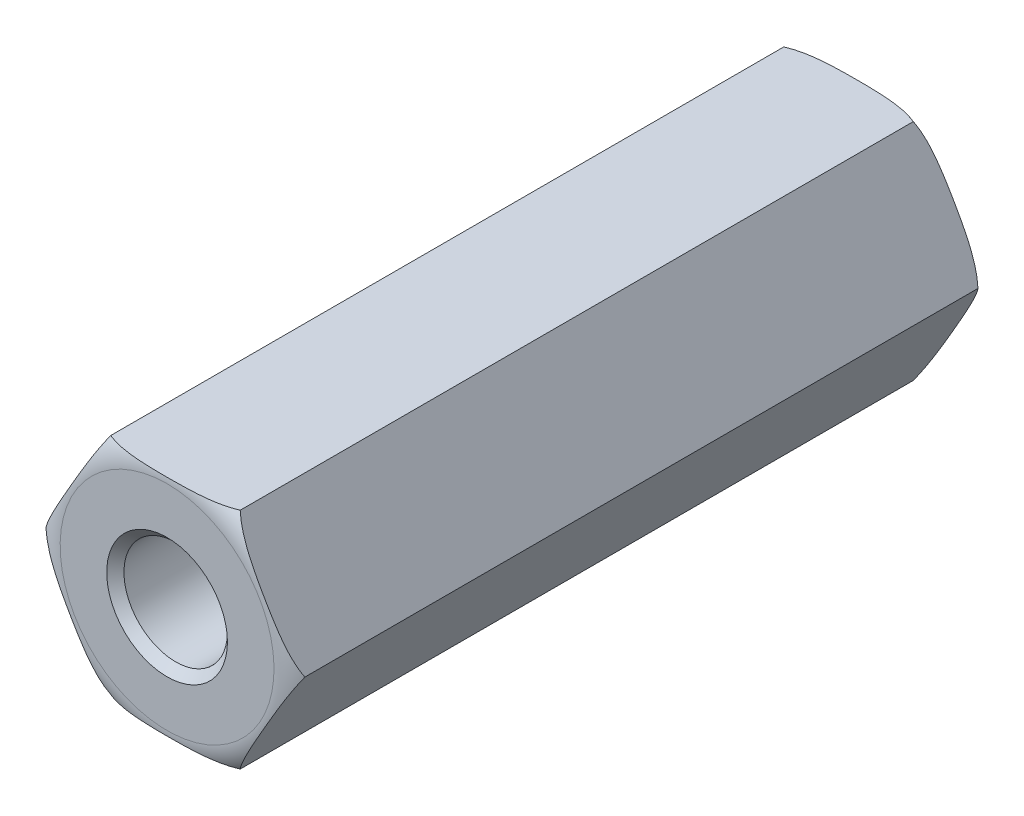
SolidWorks part; units mm, degrees
ref_plane "Front Plane" through (0, 0, 0) normal (0, 0, 1) x (1, 0, 0)
ref_plane "Top Plane" through (0, 0, 0) normal (0, 1, 0) x (1, 0, 0)
ref_plane "Right Plane" through (0, 0, 0) normal (1, 0, 0) x (0, 0, -1)
sketch "Sketch2" plane through (0, 0, 0) normal (0, 0, 1) x (1, 0, 0)
  circle A0 centre (0, 0) radius 1.5
  dimension "D1" = 3
sketch "Sketch3" plane through (0, 0, 0) normal (0, 0, 1) x (1, 0, 0)
  line L1 (3.7528, 0) -> (1.8764, 3.25)
  line L2 (1.8764, 3.25) -> (-1.8764, 3.25)
  line L3 (-1.8764, 3.25) -> (-3.7528, 0)
  line L4 (-3.7528, 0) -> (-1.8764, -3.25)
  line L5 (-1.8764, -3.25) -> (1.8764, -3.25)
  line L6 (1.8764, -3.25) -> (3.7528, 0)
  circle A0 centre (0, 0) radius 3.25 construction
extrude "Boss-Extrude2" add sketch "Sketch3" along normal blind 20
sketch "Sketch5" plane through (0, 0, 0) normal (1, 0, 0) x (0, 0, -1)
  line L0 (-20, 0) -> (-20, 3.1)
  line L1 (-19, 4.1) -> (-1, 4.1)
  line L4 (-20, 0) -> (-20.5, 0)
  line L5 (-20.5, 0) -> (-20.5, 4.9971)
  line L6 (-20.5, 4.9971) -> (1.0869, 4.9971)
  line L8 (0, 3.1) -> (0, 1.6842)
  line L9 (0, 1.6842) -> (1.0869, 1.6842)
  line L10 (1.0869, 1.6842) -> (1.0869, 4.9971)
  arc A0 (-20, 3.1) -> (-19, 4.1) centre (-19, 3.1) cw
  arc A1 (0, 3.1) -> (-1, 4.1) centre (-1, 3.1) ccw
  point P3 (-20.1287, 0)
  dimension "D1" = 1
  dimension "D3" = 1
  dimension "D2" = 3.1
  dimension "D4" = 0.5
revolve "Cut-Revolve1" cut sketch "Sketch5" angle 360 about L4
extrude "Cut-Extrude5" cut sketch "Sketch2" against normal through all and the other way through all
chamfer "Chamfer1" distance 0.25 angle 45 2 edges at (1.5, 0, 20) (1.5, 0, 0)
